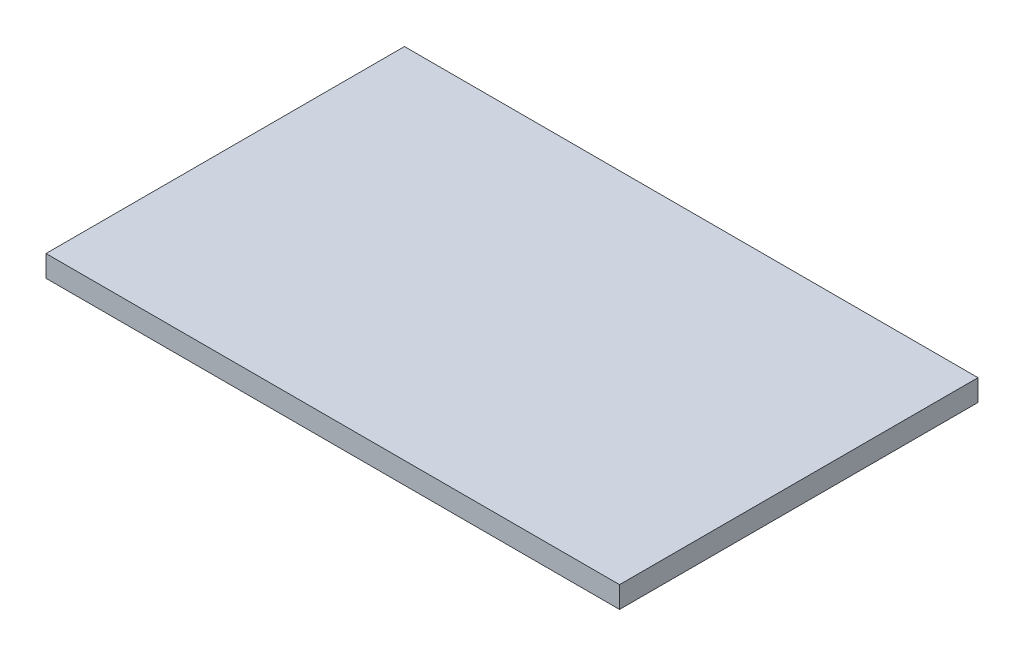
SolidWorks part; units mm, degrees
ref_plane "Front Plane" through (0, 0, 0) normal (0, 0, 1) x (1, 0, 0)
ref_plane "Top Plane" through (0, 0, 0) normal (0, 1, 0) x (1, 0, 0)
ref_plane "Right Plane" through (0, 0, 0) normal (1, 0, 0) x (0, 0, -1)
sketch "Sketch1" plane through (0, 0, 0) normal (0, 1, 0) x (1, 0, 0)
  line L1 (-29.666, 36.2639) -> (50.334, 36.2639)
  line L2 (-29.666, 36.2639) -> (-29.666, -13.7361)
  line L3 (-29.666, -13.7361) -> (50.334, -13.7361)
  line L4 (50.334, 36.2639) -> (50.334, -13.7361)
extrude "Boss-Extrude1" add sketch "Sketch1" along normal blind 3
